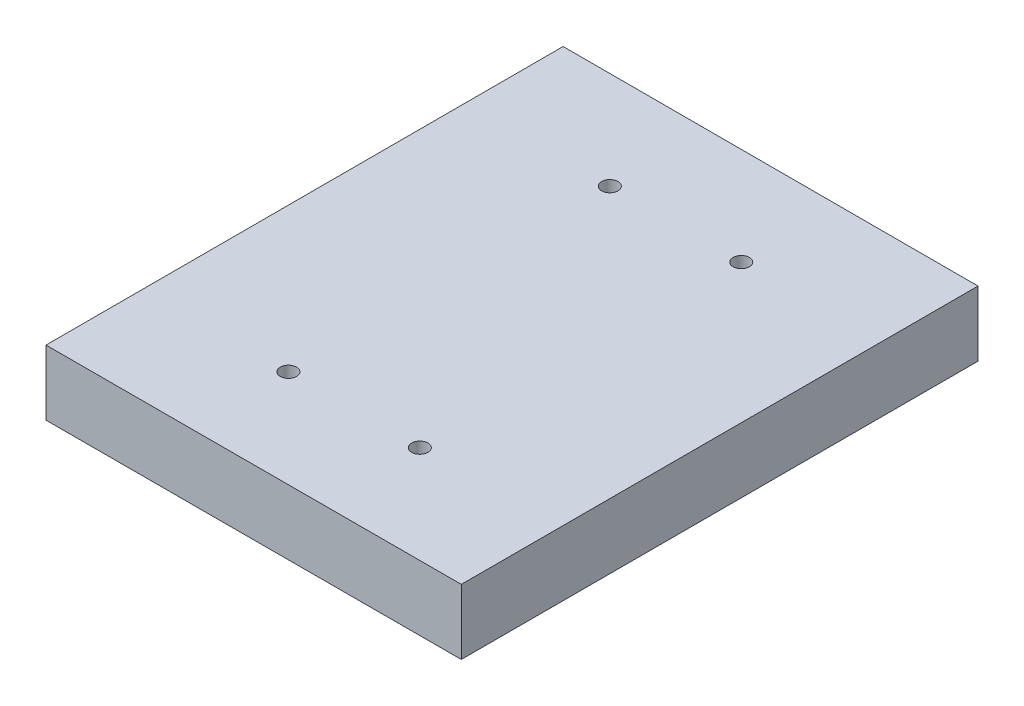
SolidWorks part; units mm, degrees
ref_plane "Front Plane" through (0, 0, 0) normal (0, 0, 1) x (1, 0, 0)
ref_plane "Top Plane" through (0, 0, 0) normal (0, 1, 0) x (1, 0, 0)
ref_plane "Right Plane" through (0, 0, 0) normal (1, 0, 0) x (0, 0, -1)
sketch "Sketch1" plane through (0, 0, 0) normal (0, 1, 0) x (1, 0, 0)
  line L0 (-56.2672, 45.4966) -> (-56.2672, -33.972)
  line L1 (-44.4881, 45.533) -> (-56.2672, 45.4966) construction
  line L2 (-44.4873, -33.917) -> (-56.2672, -33.972) construction
  line L3 (-56.2672, -33.972) -> (7.4928, -33.9068)
  line L4 (-56.2672, 45.4966) -> (-44.4881, 45.533) construction
  line L5 (-44.4881, 45.533) -> (-4.2884, 45.533) construction
  line L6 (-4.2884, 45.533) -> (7.4916, 45.4966) construction
  line L7 (7.4916, 45.4966) -> (7.4916, -33.9068)
  line L8 (-4.2884, 45.533) -> (7.4916, 45.4966) construction
  line L9 (7.4916, 45.4966) -> (-56.2672, 45.4966)
  circle A0 centre (-13.8872, 30.4966) radius 1.25
  circle A1 centre (-13.8872, -18.9034) radius 1.25
  circle A2 centre (-34.0872, -18.9034) radius 1.25
  circle A3 centre (-34.0872, 30.4966) radius 1.25
extrude "Boss-Extrude2" add sketch "Sketch1" against normal blind 10
sketch "Sketch3" plane through (0, -10, 0) normal (0, -1, 0) x (1, 0, 0)
  circle A0 centre (-13.8872, 18.9034) radius 2.5
  circle A1 centre (-34.0872, 18.9034) radius 2.5
  circle A2 centre (-13.8872, -30.4966) radius 2.5
  circle A3 centre (-34.0872, -30.4966) radius 2.5
extrude "Cut-Extrude2" cut sketch "Sketch3" against normal blind 2
